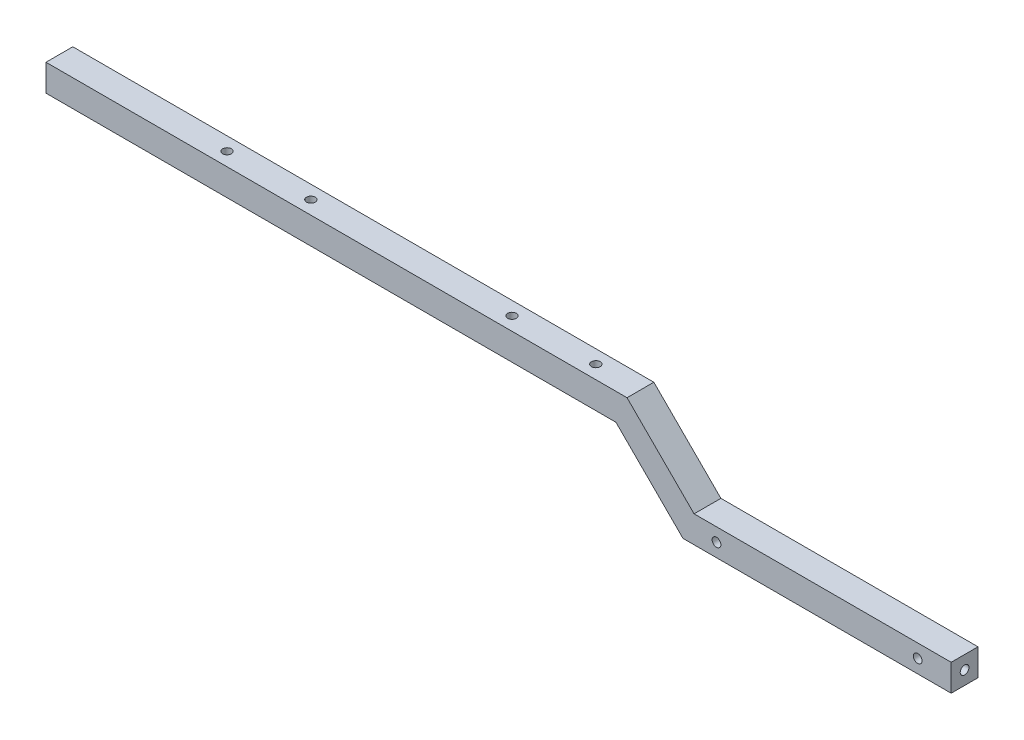
SolidWorks part; units mm, degrees
ref_plane "Front Plane" through (0, 0, 0) normal (1, 0, 0) x (0, 1, 0)
ref_plane "Top Plane" through (0, 0, 0) normal (0, 0, 1) x (0, 1, 0)
ref_plane "Right Plane" through (0, 0, 0) normal (0, 1, 0) x (-1, 0, 0)
sketch "Sketch2" plane through (0, 0, 0) normal (0, 0, 1) x (0, 1, 0)
  line L1 (-8, 65) -> (0, 65)
  line L2 (-8, 65) -> (-8, -65)
  line L3 (-8, -65) -> (0, -65)
  line L4 (0, 65) -> (0, -65)
  point P5 (0, 0)
  dimension "D1" = 8
  dimension "D2" = 130
extrude "Boss-Extrude1" add sketch "Sketch2" along normal blind 8
sketch "Sketch4" plane through (0, 0, 0) normal (0, 1, 0) x (-1, 0, 0)
  line L0 (0, 8) -> (0, 0) construction
  line L1 (-65, 8) -> (65, 8) construction
  line L2 (-65, 4) -> (0, 4) construction
  line L5 (-65, 8) -> (-65, 0) construction
  circle A0 centre (-55, 4) radius 1.3
  circle A1 centre (-30, 4) radius 1.3
  circle A4 centre (30, 4) radius 1.3
  circle A5 centre (55, 4) radius 1.3
  dimension "D1" = 2.6
  dimension "D2" = 2.6
  dimension "D4" = 30
  dimension "D3" = 25
extrude "Cut-Extrude1" cut sketch "Sketch4" against normal up to next
sketch "Sketch7" plane through (0, 0, 0) normal (0, 0, -1) x (1, 0, 0)
  line L0 (65, 8) -> (85, 28)
  line L1 (85, 28) -> (165, 28)
  line L2 (165, 28) -> (165, 20)
  line L3 (165, 20) -> (88.3137, 20)
  line L4 (88.3137, 20) -> (68.3137, 0)
  line L5 (68.3137, 0) -> (65, 0)
  line L6 (-65, 8) -> (65, 8) construction
  line L10 (65, 8) -> (-65, 8)
  line L11 (65, 0) -> (65, 8)
  line L12 (-65, 0) -> (65, 0)
  line L13 (-65, 8) -> (-65, 0)
  line L15 (65, 0) -> (65, 8)
  dimension "D1" = 8
  dimension "D2" = 8
  dimension "D3" = 80
  dimension "D4" = 20
  dimension "D6" = 135
  dimension "D5" = 0
extrude "Boss-Extrude2" add sketch "Sketch7" against normal blind 8
sketch "Sketch8" plane through (165, 0, 0) normal (1, 0, 0) x (0, 1, 0)
  line L1 (-24, 8) -> (-24, 0) construction
  line L2 (-20, 8) -> (-28, 8) construction
  line L3 (-20, 0) -> (-28, 0) construction
  circle A0 centre (-24, 4) radius 1.3
  point P3 (-24, 4)
  dimension "D1" = 2.6
extrude "Cut-Extrude3" cut sketch "Sketch8" against normal blind 10
sketch "Sketch9" plane through (0, 0, 0) normal (0, 0, -1) x (1, 0, 0)
  line L0 (165, 28) -> (85, 28) construction
  line L1 (125, 28) -> (125, 20) construction
  line L2 (88.3137, 20) -> (165, 20) construction
  circle A0 centre (95, 24) radius 1.3
  circle A1 centre (155, 24) radius 1.3
  point P8 (125, 24)
  dimension "D2" = 2.6
  dimension "D1" = 30
extrude "Cut-Extrude4" cut sketch "Sketch9" against normal up to next
sketch "Sketch10" plane through (0, 0, 8) normal (0, 0, 1) x (1, 0, 0)
  line L1 (-65, -8) -> (-105, -8)
  line L2 (-65, -8) -> (-65, 0)
  line L3 (-65, 0) -> (-105, 0)
  line L4 (-105, -8) -> (-105, 0)
  dimension "D1" = 40
extrude "Boss-Extrude3" add sketch "Sketch10" against normal blind 8
sketch "Sketch11" plane through (-105, 0, 0) normal (-1, 0, 0) x (0, -1, 0)
  line L0 (4, 8) -> (4, 0) construction
  line L1 (0, 8) -> (8, 8) construction
  line L2 (0, 0) -> (8, 0) construction
  circle A0 centre (4, 4) radius 1.3
  dimension "D1" = 2.6
extrude "Cut-Extrude5" cut sketch "Sketch11" against normal blind 10
